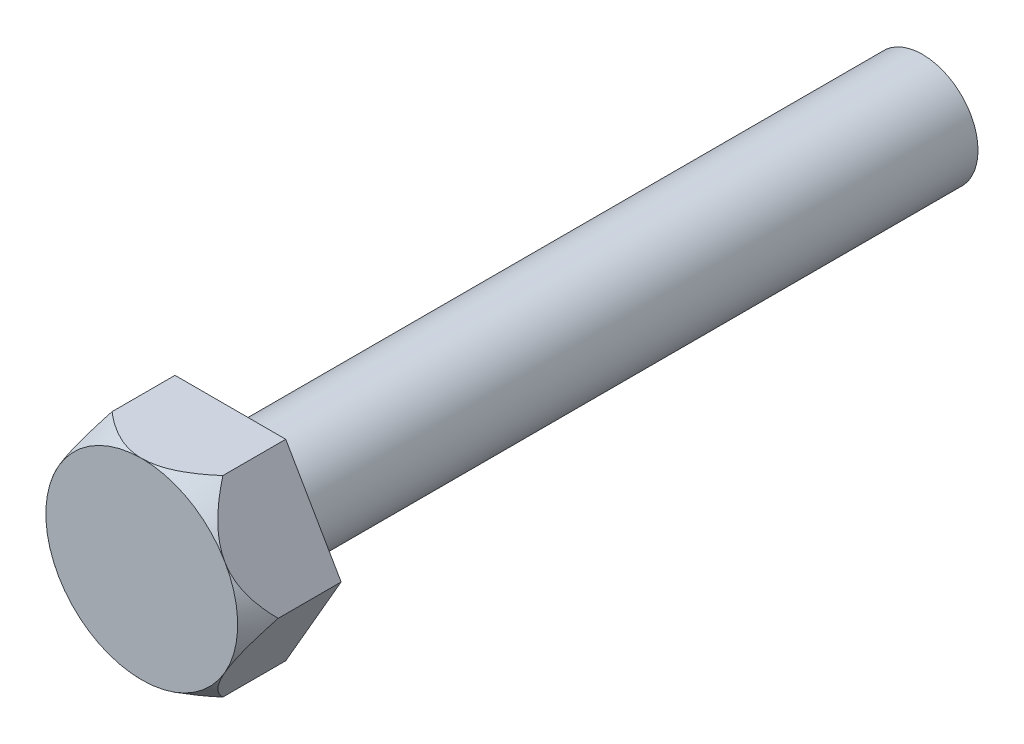
SolidWorks part; units mm, degrees
ref_plane "Front Plane" through (0, 0, 0) normal (0, 0, 1) x (1, 0, 0)
ref_plane "Top Plane" through (0, 0, 0) normal (0, 1, 0) x (1, 0, 0)
ref_plane "Right Plane" through (0, 0, 0) normal (1, 0, 0) x (0, 0, -1)
sketch "Sketch1" plane through (0, 0, 0) normal (0, 0, 1) x (1, 0, 0)
  line L1 (8, 0) -> (4, 6.9282)
  line L2 (4, 6.9282) -> (-4, 6.9282)
  line L3 (-4, 6.9282) -> (-8, 0)
  line L4 (-8, 0) -> (-4, -6.9282)
  line L5 (-4, -6.9282) -> (4, -6.9282)
  line L6 (4, -6.9282) -> (8, 0)
  circle A0 centre (0, 0) radius 6.9282 construction
  dimension "D1" = 16
extrude "Boss-Extrude1" add sketch "Sketch1" along normal blind 6.4
sketch "Sketch2" plane through (0, 0, 6.4) normal (0, 0, 1) x (1, 0, 0)
  line L0 (8, 0) -> (4, 6.9282) construction
  circle A0 centre (0, 0) radius 6.9282
extrude "Cut-Extrude1" cut sketch "Sketch2" against normal blind 6.4 draft 30 flip side to cut
sketch "Sketch3" plane through (0, 0, 0) normal (0, 0, -1) x (-1, 0, 0)
  circle A0 centre (0, 0) radius 4
  dimension "D1" = 8
extrude "Boss-Extrude2" add sketch "Sketch3" along normal blind 50
